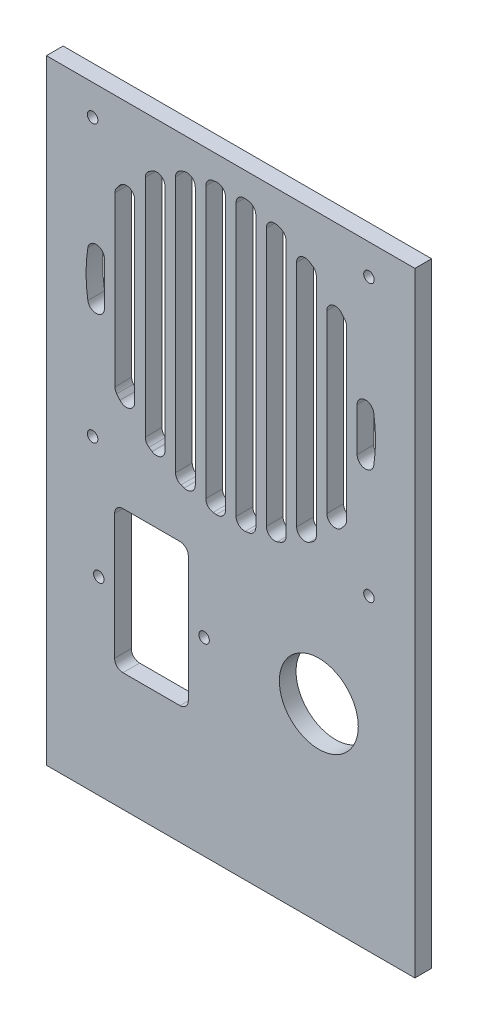
SolidWorks part; units mm, degrees
ref_plane "Front Plane" through (0, 0, 0) normal (0, 0, 1) x (1, 0, 0)
ref_plane "Top Plane" through (0, 0, 0) normal (0, 1, 0) x (1, 0, 0)
ref_plane "Right Plane" through (0, 0, 0) normal (1, 0, 0) x (0, 0, -1)
sketch "Sketch1" plane through (0, 0, 0) normal (0, 0, 1) x (1, 0, 0)
  line L1 (-70, 116.75) -> (70, 116.75)
  line L2 (-70, 116.75) -> (-70, -116.75)
  line L3 (-70, -116.75) -> (70, -116.75)
  line L4 (70, 116.75) -> (70, -116.75)
  line L5 (-70, 116.75) -> (70, -116.75) construction
  line L6 (-70, -116.75) -> (70, 116.75) construction
  point P0 (0, 0)
  dimension "D1" = 233.5
  dimension "D2" = 140
extrude "Boss-Extrude1" add sketch "Sketch1" along normal blind 6.35
sketch "Sketch2" plane through (0, 0, 6.35) normal (0, 0, 1) x (1, 0, 0)
  line L0 (-58.1334, -44.75) -> (-2.0527, -44.75) construction
  line L1 (-2.0527, -44.75) -> (-30.0931, -44.75) construction
  line L2 (-30.0931, -44.75) -> (-30.0931, 59.9614) construction
  line L3 (-30.0931, 59.9614) -> (-30.0931, -2.6688) construction
  line L4 (-70, -116.75) -> (70, -116.75) construction
  line L5 (-44.0931, -17.75) -> (-16.0931, -17.75)
  line L6 (-44.0931, -17.75) -> (-44.0931, -71.75)
  line L7 (-44.0931, -71.75) -> (-16.0931, -71.75)
  line L8 (-16.0931, -17.75) -> (-16.0931, -71.75)
  line L9 (-44.0931, -17.75) -> (-16.0931, -71.75) construction
  line L10 (-44.0931, -71.75) -> (-16.0931, -17.75) construction
  circle A0 centre (-50.0931, -44.75) radius 2
  circle A1 centre (-10.0931, -44.75) radius 2
  point P7 (-30.0931, 28.6463)
  dimension "D1" = 4
  dimension "D2" = 20
  dimension "D3" = 28
  dimension "D4" = 54
  dimension "D5" = 45
extrude "Cut-Extrude1" cut sketch "Sketch2" against normal through all
fillet "Fillet1" radius 3.175 4 edges at (-44.0931, -71.75, 3.175) (-16.0931, -71.75, 3.175) (-44.0931, -17.75, 3.175) (-16.0931, -17.75, 3.175)
sketch "Sketch3" plane through (0, 0, 6.35) normal (0, 0, 1) x (1, 0, 0)
  line L0 (-50.0931, -44.75) -> (88.7599, -44.75) construction
  circle A0 centre (33.4977, -44.75) radius 15
  dimension "D1" = 30
extrude "Cut-Extrude2" cut sketch "Sketch3" against normal through all
sketch "Sketch4" plane through (0, 0, 6.35) normal (0, 0, 1) x (1, 0, 0)
  line L0 (-59.9456, 112.7344) -> (60.0544, -7.2656) construction
  line L1 (60.0544, -7.2656) -> (60.0544, 112.7344) construction
  line L2 (60.0544, 112.7344) -> (-59.9456, 112.7344) construction
  line L3 (-59.9456, 112.7344) -> (-59.9456, -7.2656) construction
  line L4 (-59.9456, -7.2656) -> (60.0544, -7.2656) construction
  line L5 (-59.9456, -7.2656) -> (60.0544, 112.7344) construction
  circle A0 centre (-52.4456, 105.2344) radius 2
  circle A1 centre (52.5544, 105.2344) radius 2
  circle A2 centre (52.5544, 0.2344) radius 2
  circle A3 centre (-52.4456, 0.2344) radius 2
  point P6 (0.0544, 52.7344)
  point P16 (0.0544, 52.7344)
  dimension "D3" = 105
  dimension "D4" = 4
  dimension "D1" = 120
  dimension "D2" = 4
extrude "Cut-Extrude3" cut sketch "Sketch4" against normal through all
sketch "Sketch5" plane through (0, 0, 6.35) normal (0, 0, 1) x (1, 0, 0)
  line L0 (-52.4456, 105.2344) -> (52.5544, 0.2344) construction
  line L1 (9.5544, 111.239) -> (9.5544, -5.7701)
  line L2 (52.5544, 105.2344) -> (-52.4456, 0.2344) construction
  line L3 (-1.9456, 111.239) -> (2.0544, 111.239)
  line L4 (-1.9456, 111.239) -> (-1.9456, -5.7701)
  line L5 (-1.9456, -5.7701) -> (2.0544, -5.7701)
  line L6 (2.0544, 111.239) -> (2.0544, -5.7701)
  line L7 (-1.9456, 111.239) -> (2.0544, -5.7701) construction
  line L8 (-1.9456, -5.7701) -> (2.0544, 111.239) construction
  line L9 (9.5544, 111.239) -> (13.5544, 111.239)
  line L10 (13.5544, 111.239) -> (13.5544, -5.7701)
  line L11 (9.5544, -5.7701) -> (13.5544, -5.7701)
  line L12 (21.0544, 111.239) -> (21.0544, -5.7701)
  line L13 (21.0544, 111.239) -> (25.0544, 111.239)
  line L14 (25.0544, 111.239) -> (25.0544, -5.7701)
  line L15 (21.0544, -5.7701) -> (25.0544, -5.7701)
  line L16 (32.5544, 111.239) -> (32.5544, -5.7701)
  line L17 (32.5544, 111.239) -> (36.5544, 111.239)
  line L18 (36.5544, 111.239) -> (36.5544, -5.7701)
  line L19 (32.5544, -5.7701) -> (36.5544, -5.7701)
  line L20 (44.0544, 111.239) -> (44.0544, -5.7701)
  line L21 (44.0544, 111.239) -> (48.0544, 111.239)
  line L22 (48.0544, 111.239) -> (48.0544, -5.7701)
  line L23 (44.0544, -5.7701) -> (48.0544, -5.7701)
  line L24 (-13.4456, 111.239) -> (-13.4456, -5.7701)
  line L25 (-13.4456, 111.239) -> (-9.4456, 111.239)
  line L26 (-9.4456, 111.239) -> (-9.4456, -5.7701)
  line L27 (-13.4456, -5.7701) -> (-9.4456, -5.7701)
  line L28 (-24.9456, 111.239) -> (-24.9456, -5.7701)
  line L29 (-24.9456, 111.239) -> (-20.9456, 111.239)
  line L30 (-20.9456, 111.239) -> (-20.9456, -5.7701)
  line L31 (-24.9456, -5.7701) -> (-20.9456, -5.7701)
  line L32 (-36.4456, 111.239) -> (-36.4456, -5.7701)
  line L33 (-36.4456, 111.239) -> (-32.4456, 111.239)
  line L34 (-32.4456, 111.239) -> (-32.4456, -5.7701)
  line L35 (-36.4456, -5.7701) -> (-32.4456, -5.7701)
  line L36 (-47.9456, 111.239) -> (-47.9456, -5.7701)
  line L37 (-47.9456, 111.239) -> (-43.9456, 111.239)
  line L38 (-43.9456, 111.239) -> (-43.9456, -5.7701)
  line L39 (-47.9456, -5.7701) -> (-43.9456, -5.7701)
  circle A0 centre (0.0544, 52.7344) radius 55
  point P4 (0.0544, 52.7344)
  dimension "D1" = 110
  dimension "D2" = 4
  dimension "D3" = 5
extrude "Cut-Extrude4" cut sketch "Sketch5" against normal blind 6.35 contours L36 A0 | L32 A0 L38 | L28 A0 L34 | L24 A0 L30 | L4 A0 L26 | L1 A0 L6 | L12 A0 L10 | L16 A0 L14 | L20 A0 L18 | L22 A0
fillet "Fillet2" radius 3.175 36 edges at (-47.9456, 79.5859, 3.175) (-47.9456, 25.883, 3.175) (-24.9456, 101.7242, 3.175) (-24.9456, 3.7446, 3.175) (-32.4456, 8.3638, 3.175) (-32.4456, 97.105, 3.175) (-1.9456, 107.698, 3.175) (-1.9456, -2.2292, 3.175) (-9.4456, -1.4389, 3.175) (-9.4456, 106.9077, 3.175) (21.0544, 103.5675, 3.175) (21.0544, 1.9013, 3.175) (13.5544, -0.583, 3.175) (13.5544, 106.0519, 3.175) (44.0544, 85.7344, 3.175) (44.0544, 19.7344, 3.175) (36.5544, 11.5914, 3.175) (36.5544, 93.8775, 3.175) (48.0544, 25.883, 3.175) (48.0544, 79.5859, 3.175) (32.5544, 97.105, 3.175) (32.5544, 8.3638, 3.175) (25.0544, 3.7446, 3.175) (25.0544, 101.7242, 3.175) (9.5544, 106.9077, 3.175) (9.5544, -1.4389, 3.175) (2.0544, -2.2292, 3.175) (2.0544, 107.698, 3.175) (-13.4456, 106.0519, 3.175) (-13.4456, -0.583, 3.175) (-20.9456, 1.9013, 3.175) (-20.9456, 103.5675, 3.175) (-36.4456, 93.8775, 3.175) (-36.4456, 11.5914, 3.175) (-43.9456, 19.7344, 3.175) (-43.9456, 85.7344, 3.175)
